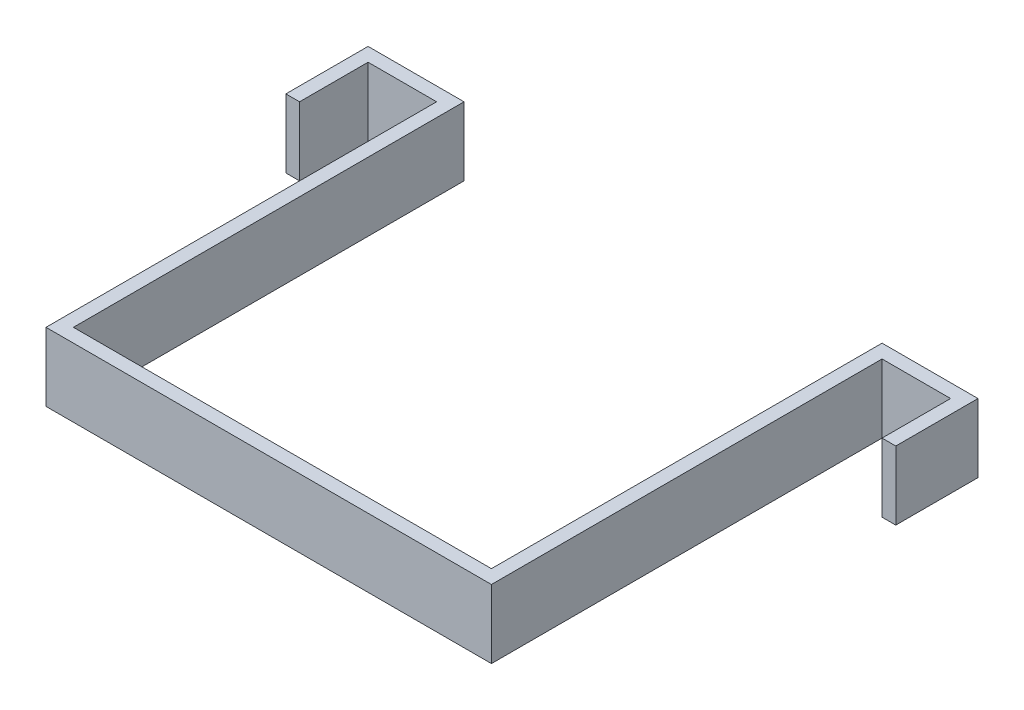
SolidWorks part; units mm, degrees
ref_plane "Front Plane" through (0, 0, 0) normal (0, 0, 1) x (1, 0, 0)
ref_plane "Top Plane" through (0, 0, 0) normal (0, 1, 0) x (1, 0, 0)
ref_plane "Right Plane" through (0, 0, 0) normal (1, 0, 0) x (0, 0, -1)
sketch "Sketch1" plane through (0, 0, 0) normal (0, 1, 0) x (1, 0, 0)
  line L1 (0, 0) -> (0, 82.8524) construction
  line L2 (-107.95, -25.4) -> (-107.95, 0)
  line L3 (-107.95, 0) -> (-82.55, 0)
  line L4 (-113.03, -25.4) -> (-113.03, 5.08)
  line L5 (-113.03, 5.08) -> (-77.47, 5.08)
  line L6 (-77.47, 5.08) -> (-77.47, -139.7)
  line L7 (-77.47, -139.7) -> (77.47, -139.7)
  line L8 (-77.47, -139.7) -> (-77.47, -144.78) construction
  line L9 (82.55, -144.78) -> (-82.55, -144.78)
  line L10 (-82.55, -144.78) -> (-82.55, 0)
  line L11 (-113.03, -25.4) -> (-107.95, -25.4)
  line L12 (-107.95, 5.08) -> (-107.95, 0) construction
  line L13 (-82.55, 0) -> (-77.47, 0) construction
  line L14 (82.55, 0) -> (77.47, 0) construction
  line L15 (107.95, 5.08) -> (107.95, 0) construction
  line L16 (77.47, -139.7) -> (77.47, -144.78) construction
  line L17 (113.03, -25.4) -> (107.95, -25.4)
  line L18 (82.55, -144.78) -> (82.55, 0)
  line L19 (77.47, 5.08) -> (77.47, -139.7)
  line L20 (113.03, 5.08) -> (77.47, 5.08)
  line L21 (113.03, -25.4) -> (113.03, 5.08)
  line L22 (107.95, 0) -> (82.55, 0)
  line L23 (107.95, -25.4) -> (107.95, 0)
  point P1 (0, 0)
  point P4 (0, 0)
  point P15 (0, -139.7)
  point P28 (0, -144.78)
  dimension "D1" = 165.1
  dimension "D2" = 5.08
  dimension "D3" = 215.9
  dimension "D6" = 139.7
  dimension "D7" = 25.4
extrude "Boss-Extrude1" add sketch "Sketch1" along normal mid plane 25.4
